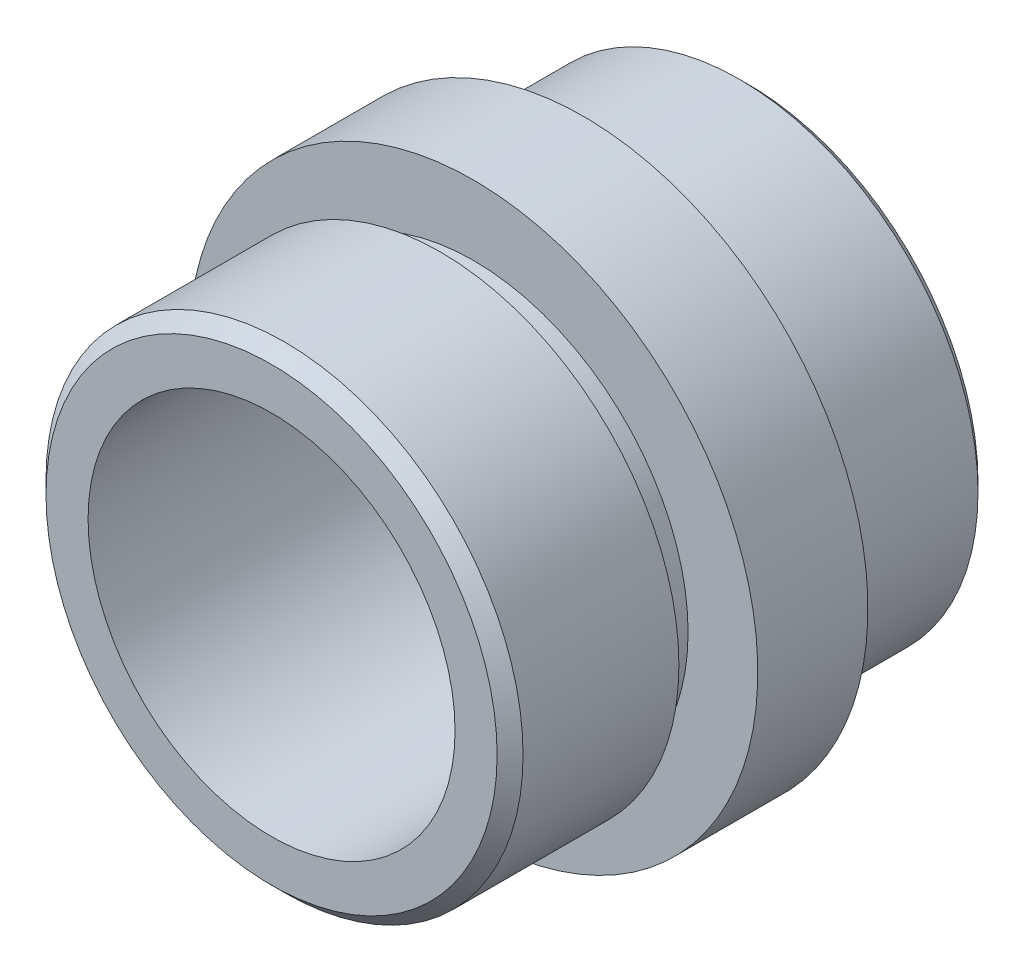
SolidWorks part; units mm, degrees
ref_plane "Спереди" through (0, 0, 0) normal (0, 0, 1) x (1, 0, 0)
ref_plane "Сверху" through (0, 0, 0) normal (0, 1, 0) x (1, 0, 0)
ref_plane "Справа" through (0, 0, 0) normal (1, 0, 0) x (0, 0, -1)
ref_plane "Плоскость4" through (0, 0, 0) normal (0, -1, 0) x (1, 0, 0)
sketch "Эскиз1" plane through (0, 0, 0) normal (0, -1, 0) x (1, 0, 0)
  line L0 (11.7, 16.8) -> (13, 16.8)
  line L1 (13, 16.8) -> (13, 25.2929)
  line L2 (13, 25.2929) -> (12.2929, 26)
  line L3 (12.2929, 26) -> (10, 26)
  line L4 (10, 26) -> (10, 1)
  line L5 (10, 1) -> (11, 0)
  line L6 (11, 0) -> (12.5, 0)
  line L7 (12.5, 0) -> (13, 0.5)
  line L8 (13, 0.5) -> (13, 7.7)
  line L9 (13, 7.7) -> (11.7, 7.7)
  line L10 (11.7, 7.7) -> (11.7, 9)
  line L11 (11.7, 9) -> (15.5, 9)
  line L12 (15.5, 9) -> (15.5, 15)
  line L13 (15.5, 15) -> (11.7, 15)
  line L14 (11.7, 15) -> (11.7, 16.8)
  line L15 (0, 26.005) -> (0, -0.005) construction
revolve "Повернуть1" add sketch "Эскиз1" angle 360 about L15
